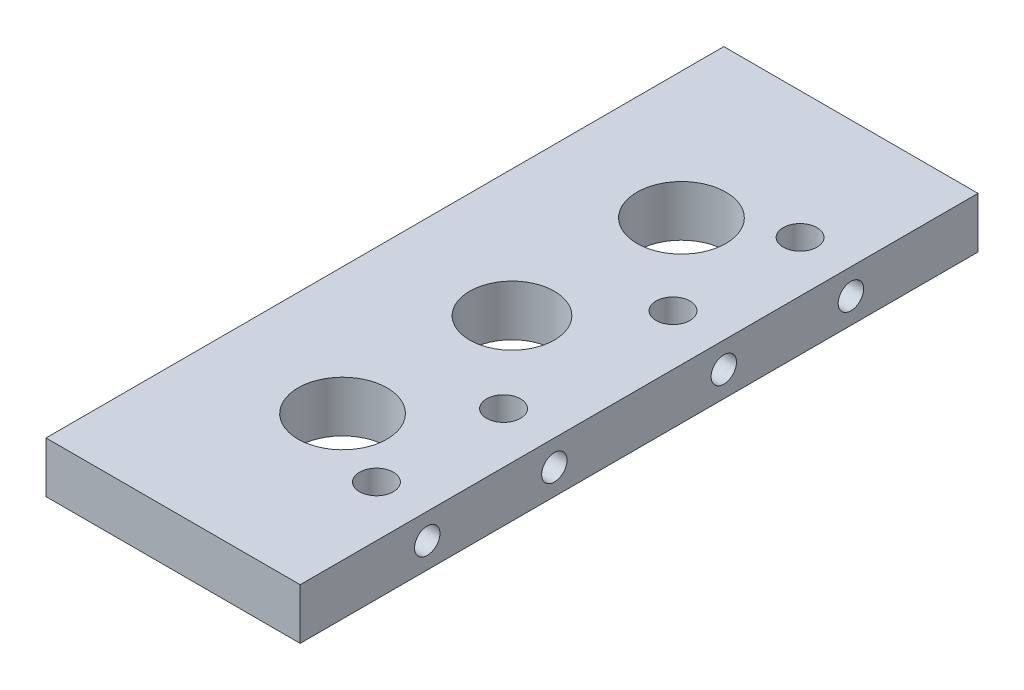
SolidWorks part; units mm, degrees
material "Beech"
ref_plane "Front Plane" through (0, 0, 0) normal (0, 0, 1) x (1, 0, 0)
ref_plane "Top Plane" through (0, 0, 0) normal (0, 1, 0) x (1, 0, 0)
ref_plane "Right Plane" through (0, 0, 0) normal (1, 0, 0) x (0, 0, -1)
sketch "Sketch1" plane through (0, 0, 0) normal (0, 1, 0) x (1, 0, 0)
  line L1 (30, -80) -> (-30, -80)
  line L2 (30, -80) -> (30, 80)
  line L3 (30, 80) -> (-30, 80)
  line L4 (-30, -80) -> (-30, 80)
  line L5 (30, -80) -> (-30, 80) construction
  line L6 (30, 80) -> (-30, -80) construction
  circle A0 centre (0, 0) radius 10
  circle A1 centre (0, 40) radius 10.5
  circle A2 centre (0, -40) radius 10.5
  dimension "D1" = 20
  dimension "D2" = 21
  dimension "D3" = 21
  dimension "D4" = 40
  dimension "D5" = 40
  dimension "D6" = 60
  dimension "D7" = 160
extrude "Boss-Extrude1" add sketch "Sketch1" along normal blind 12
sketch "Sketch2" plane through (0, 12, 0) normal (0, 1, 0) x (1, 0, 0)
  line L0 (18, 63.1588) -> (18, -66.7376) construction
  line L1 (32.2293, 0) -> (-33.4675, 0) construction
  line L2 (30, -80) -> (30, 80) construction
  circle A0 centre (18, 50) radius 4
  circle A1 centre (18, -50) radius 4
  circle A2 centre (18, -20) radius 4
  circle A3 centre (18, 20) radius 4
  dimension "D1" = 8
  dimension "D2" = 8
  dimension "D3" = 8
  dimension "D4" = 8
  dimension "D5" = 20
  dimension "D6" = 20
  dimension "D7" = 30
  dimension "D8" = 30
  dimension "D9" = 12
extrude "Cut-Extrude1" cut sketch "Sketch2" against normal up to next
sketch "Sketch3" plane through (30, 0, 0) normal (1, 0, 0) x (0, 0, -1)
  line L0 (61.4148, 6) -> (-66.4885, 6) construction
  line L1 (0, 14.5041) -> (0, -4.8635) construction
  circle A0 centre (50, 6) radius 3
  circle A1 centre (20, 6) radius 3
  circle A2 centre (-20, 6) radius 3
  circle A3 centre (-50, 6) radius 3
  dimension "D1" = 6
  dimension "D2" = 6
  dimension "D3" = 6
  dimension "D4" = 6
  dimension "D5" = 20
  dimension "D6" = 20
  dimension "D7" = 30
  dimension "D8" = 30
extrude "Cut-Extrude2" cut sketch "Sketch3" against normal up to next
